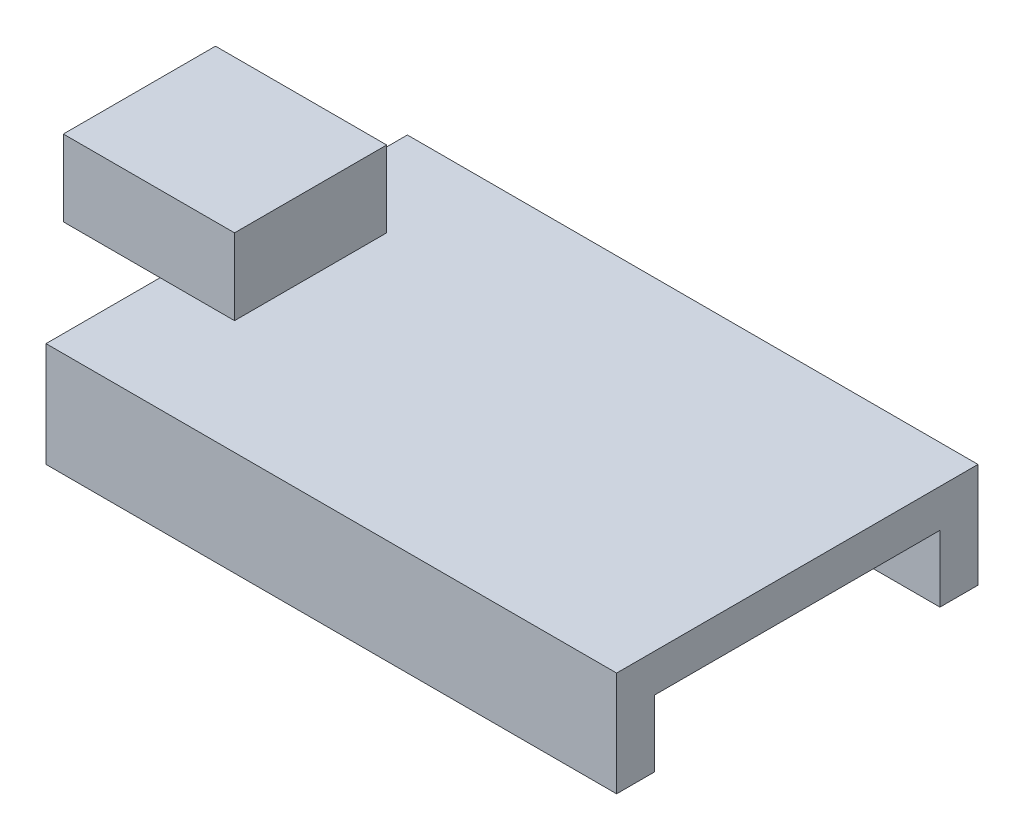
SolidWorks part; units mm, degrees
ref_plane "Front Plane" through (0, 0, 0) normal (0, 0, 1) x (1, 0, 0)
ref_plane "Top Plane" through (0, 0, 0) normal (0, 1, 0) x (1, 0, 0)
ref_plane "Right Plane" through (0, 0, 0) normal (1, 0, 0) x (0, 0, -1)
sketch "Sketch1" plane through (0, 0, 0) normal (0, 1, 0) x (1, 0, 0)
  line L1 (0, 0) -> (30, 0)
  line L2 (0, 0) -> (0, -2)
  line L3 (0, -2) -> (30, -2)
  line L4 (30, 0) -> (30, -2)
  line L5 (0, -17) -> (30, -17)
  line L6 (0, -17) -> (0, -19)
  line L7 (0, -19) -> (30, -19)
  line L8 (30, -17) -> (30, -19)
  dimension "D1" = 30
  dimension "D2" = 30
  dimension "D3" = 2
  dimension "D4" = 2
  dimension "D5" = 15
extrude "Boss-Extrude1" add sketch "Sketch1" along normal blind 3.5
sketch "Sketch2" plane through (0, 3.5, 0) normal (0, 1, 0) x (1, 0, 0)
  line L1 (0, 0) -> (30, 0)
  line L2 (0, 0) -> (0, -19)
  line L3 (0, -19) -> (30, -19)
  line L4 (30, 0) -> (30, -19)
extrude "Boss-Extrude2" add sketch "Sketch2" along normal blind 2
sketch "Sketch3" plane through (0, 5.5, 0) normal (0, 1, 0) x (1, 0, 0)
  line L0 (30, 0) -> (0, 0) construction
  line L1 (-5.0879, -5) -> (3.9121, -5)
  line L2 (-5.0879, -5) -> (-5.0879, -13)
  line L3 (-5.0879, -13) -> (3.9121, -13)
  line L4 (3.9121, -5) -> (3.9121, -13)
  dimension "D1" = 8
  dimension "D2" = 5
  dimension "D3" = 9
extrude "Boss-Extrude3" add sketch "Sketch3" along normal blind 4
